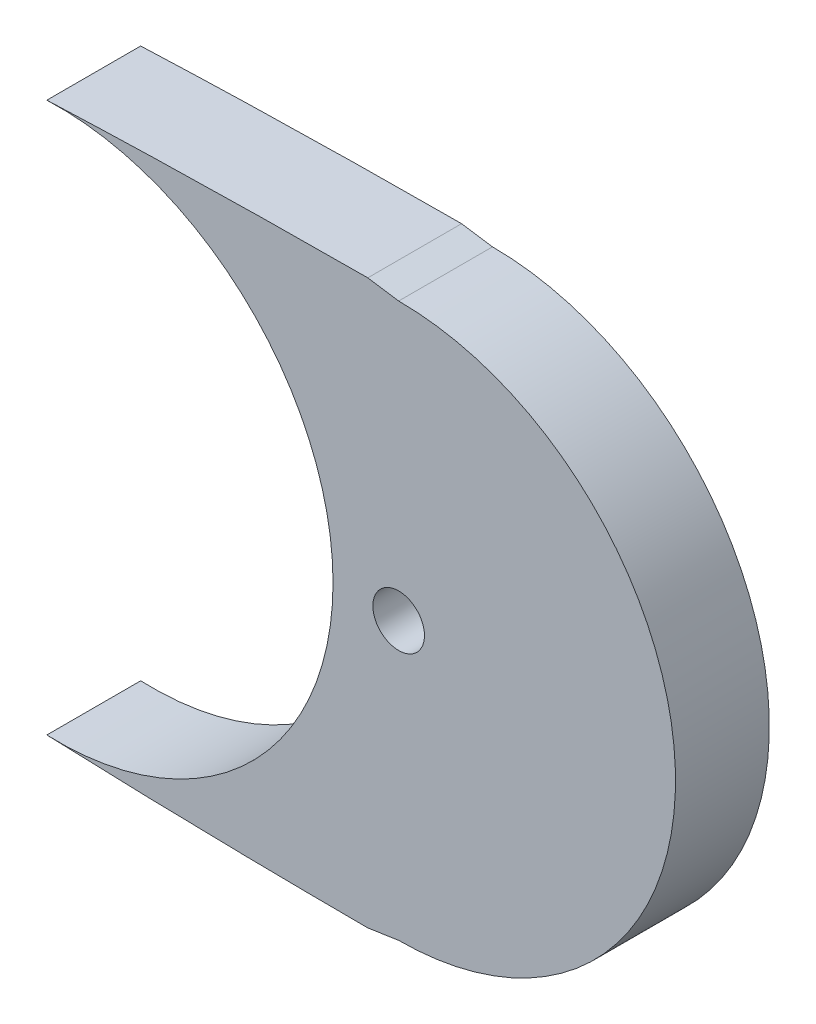
SolidWorks part; units mm, degrees
ref_plane "Front Plane" through (0, 0, 0) normal (0, 0, 1) x (1, 0, 0)
ref_plane "Top Plane" through (0, 0, 0) normal (0, 1, 0) x (1, 0, 0)
ref_plane "Right Plane" through (0, 0, 0) normal (1, 0, 0) x (0, 0, -1)
curve "Curve2"
  spline degree 3 poles (300, 0.378, 0) (299.8459, 0.3996, 0) (299.2303, 0.4859, 0) (297.8489, 0.6785, 0) (295.556, 0.9968, 0) (292.3657, 1.4334, 0) (288.2979, 1.9834, 0) (283.3772, 2.6357, 0) (277.6343, 3.3815, 0) (271.1045, 4.209, 0) (263.8281, 5.1072, 0) (255.8498, 6.0628, 0) (247.219, 7.0642, 0) (237.9888, 8.0979, 0) (228.216, 9.1511, 0) (217.9611, 10.2107, 0) (207.2872, 11.2632, 0) (196.2601, 12.2937, 0) (184.9478, 13.2887, 0) (173.4201, 14.2316, 0) (161.7479, 15.107, 0) (150.0032, 15.8986, 0) (138.2584, 16.5898, 0) (126.5858, 17.1634, 0) (115.0575, 17.6038, 0) (103.7442, 17.8968, 0) (92.7158, 18.028, 0) (82.0402, 17.9871, 0) (71.7831, 17.7661, 0) (62.0077, 17.3595, 0) (52.7741, 16.7661, 0) (44.1391, 15.9878, 0) (36.1555, 15.0306, 0) (28.872, 13.9026, 0) (22.3327, 12.6157, 0) (16.576, 11.1845, 0) (11.6345, 9.6228, 0) (7.5334, 7.9452, 0) (4.2857, 6.163, 0) (1.8965, 4.2728, 0) (0.3663, 2.2288, 0) (-0.1707, 0, 0) (0.3663, -2.2288, 0) (1.8965, -4.2728, 0) (4.2857, -6.163, 0) (7.5334, -7.9452, 0) (11.6345, -9.6228, 0) (16.576, -11.1845, 0) (22.3327, -12.6157, 0) (28.872, -13.9026, 0) (36.1555, -15.0306, 0) (44.1391, -15.9878, 0) (52.7741, -16.7661, 0) (62.0077, -17.3595, 0) (71.7831, -17.7661, 0) (82.0402, -17.9871, 0) (92.7158, -18.028, 0) (103.7442, -17.8968, 0) (115.0575, -17.6038, 0) (126.5858, -17.1634, 0) (138.2584, -16.5898, 0) (150.0032, -15.8986, 0) (161.7479, -15.107, 0) (173.4201, -14.2316, 0) (184.9478, -13.2887, 0) (196.2601, -12.2937, 0) (207.2872, -11.2632, 0) (217.9611, -10.2107, 0) (228.216, -9.1511, 0) (237.9888, -8.0979, 0) (247.219, -7.0642, 0) (255.8498, -6.0628, 0) (263.8281, -5.1072, 0) (271.1045, -4.209, 0) (277.6343, -3.3815, 0) (283.3772, -2.6357, 0) (288.2979, -1.9834, 0) (292.3657, -1.4334, 0) (295.556, -0.9968, 0) (297.8489, -0.6785, 0) (299.2303, -0.4859, 0) (299.8459, -0.3996, 0) (300, -0.378, 0) knots 0 0 0 0 0.000763 0.003048 0.006841 0.012116 0.018841 0.026973 0.03646 0.047243 0.059254 0.072417 0.086651 0.101866 0.117969 0.134858 0.152428 0.170572 0.189175 0.208122 0.227297 0.24658 0.265853 0.284997 0.303895 0.322433 0.340499 0.357984 0.374788 0.390812 0.405965 0.420162 0.433328 0.445394 0.456301 0.466004 0.474472 0.481696 0.487704 0.492583 0.496544 0.5 0.503456 0.507417 0.512296 0.518304 0.525528 0.533996 0.543699 0.554606 0.566672 0.579838 0.594035 0.609188 0.625212 0.642016 0.659501 0.677567 0.696105 0.715003 0.734147 0.75342 0.772703 0.791878 0.810825 0.829428 0.847572 0.865142 0.882031 0.898134 0.913349 0.927583 0.940746 0.952757 0.96354 0.973027 0.981159 0.987884 0.993159 0.996952 0.999237 1 1 1 1
sketch "Sketch2" plane through (0, 0, 0) normal (0, 0, 1) x (1, 0, 0)
  line L0 (0, 0) -> (300.3287, 0) construction
  line L9 (300, 0.378) -> (300, -0.378)
  line L17 (90, 18.0052) -> (90, -18.0052)
  line L20 (25.2817, 12.903) -> (25.2817, -12.903)
  line L21 (46.6322, 16.1183) -> (46.6322, -16.1183)
  line L22 (68.2099, 17.5933) -> (68.2099, -17.5933)
  line L23 (131.5031, 16.8963) -> (131.5031, -16.8963)
  line L24 (173.2123, 14.1909) -> (173.2123, -14.1909)
  line L25 (215.2898, -10.4186) -> (215.2898, 10.4186)
  line L26 (257.3103, -5.8439) -> (257.3103, 5.8439)
  arc A0 (300, -0.378) -> (300, 0.378) centre (299.947, 0) ccw
  arc A3 (45, 16.0354) -> (45, -16.0354) centre (46.6322, 0) ccw
  arc A5 (67.5, -17.5789) -> (67.5, 17.5789) centre (68.2099, 0) cw
  arc A6 (22.5, 12.5996) -> (22.5, -12.5996) centre (25.2817, 0) ccw
  arc A7 (258, -5.8031) -> (258, 5.8031) centre (257.3103, 0) cw
  arc A8 (216.3287, -10.3667) -> (216.3287, 10.3667) centre (215.2898, 0) cw
  arc A9 (174.3287, -14.147) -> (174.3287, 14.147) centre (173.2123, 0) cw
  arc A11 (132.3287, -16.8761) -> (132.3287, 16.8761) centre (131.5031, 0) cw
  arc A12 (90, -18.0052) -> (90, 18.0052) centre (89.9987, 0) cw
  arc A13 (22.5, 12.5996) -> (22.5, -12.5996) centre (25.2817, 0) cw
  arc A14 (45, 16.0354) -> (45, -16.0354) centre (46.6322, 0) cw
  arc A15 (67.5, 17.5789) -> (67.5, -17.5789) centre (68.2099, 0) cw
  arc A16 (90, -18.0052) -> (90, 18.0052) centre (90, 0) ccw
  arc A17 (132.3287, 16.8761) -> (132.3287, -16.8761) centre (131.5031, 0) cw
  arc A18 (174.3287, 14.147) -> (174.3287, -14.147) centre (173.2123, 0) cw
  arc A19 (216.3287, 10.3667) -> (216.3287, -10.3667) centre (215.2898, 0) cw
  arc A20 (257.9987, 5.8032) -> (257.9987, -5.8032) centre (257.309, 0) cw
  circle A21 centre (25.2817, 0) radius 12.903
  circle A22 centre (257.3103, 0) radius 5.8439
  circle A23 centre (68.2099, 0) radius 2.65
  circle A24 centre (90, 0) radius 1.65
  spline S0 degree 3 poles (925.2225, 2929.7557) (439.7439, -25.8231) (369.6404, -9.3304) (297.8489, 0.6785) (295.556, 0.9968) (292.3657, 1.4334) (288.2979, 1.9834) (283.3772, 2.6357) (277.6343, 3.3815) (271.1045, 4.209) (263.8281, 5.1072) (255.8498, 6.0628) (247.219, 7.0642) (237.9888, 8.0979) (228.216, 9.1511) (217.9611, 10.2107) (207.2872, 11.2632) (196.2601, 12.2937) (184.9478, 13.2887) (173.4201, 14.2316) (161.7479, 15.107) (150.0032, 15.8986) (138.2584, 16.5898) (126.5858, 17.1634) (115.0575, 17.6038) (103.7442, 17.8968) (92.7158, 18.028) (82.0402, 17.9871) (71.7831, 17.7661) (62.0077, 17.3595) (52.7741, 16.7661) (44.1391, 15.9878) (36.1555, 15.0306) (28.872, 13.9026) (22.3327, 12.6157) (16.576, 11.1845) (11.6345, 9.6228) (7.5334, 7.9452) (4.2857, 6.163) (1.8965, 4.2728) (0.3663, 2.2288) (-0.1707, 0) (0.3663, -2.2288) (1.8965, -4.2728) (4.2857, -6.163) (7.5334, -7.9452) (11.6345, -9.6228) (16.576, -11.1845) (22.3327, -12.6157) (28.872, -13.9026) (36.1555, -15.0306) (44.1391, -15.9878) (52.7741, -16.7661) (62.0077, -17.3595) (71.7831, -17.7661) (82.0402, -17.9871) (92.7158, -18.028) (103.7442, -17.8968) (115.0575, -17.6038) (126.5858, -17.1634) (138.2584, -16.5898) (150.0032, -15.8986) (161.7479, -15.107) (173.4201, -14.2316) (184.9478, -13.2887) (196.2601, -12.2937) (207.2872, -11.2632) (217.9611, -10.2107) (228.216, -9.1511) (237.9888, -8.0979) (247.219, -7.0642) (255.8498, -6.0628) (263.8281, -5.1072) (271.1045, -4.209) (277.6343, -3.3815) (283.3772, -2.6357) (288.2979, -1.9834) (292.3657, -1.4334) (295.556, -0.9968) (297.8489, -0.6785) (369.6396, 9.3303) (439.7423, 25.8227) (925.2055, -2929.6525) knots -0.348659 -0.348659 -0.348659 -0.348659 0.000763 0.003048 0.006841 0.012116 0.018841 0.026973 0.03646 0.047243 0.059254 0.072417 0.086651 0.101866 0.117969 0.134858 0.152428 0.170572 0.189175 0.208122 0.227297 0.24658 0.265853 0.284997 0.303895 0.322433 0.340499 0.357984 0.374788 0.390812 0.405965 0.420162 0.433328 0.445394 0.456301 0.466004 0.474472 0.481696 0.487704 0.492583 0.496544 0.5 0.503456 0.507417 0.512296 0.518304 0.525528 0.533996 0.543699 0.554606 0.566672 0.579838 0.594035 0.609188 0.625212 0.642016 0.659501 0.677567 0.696105 0.715003 0.734147 0.75342 0.772703 0.791878 0.810825 0.829428 0.847572 0.865142 0.882031 0.898134 0.913349 0.927583 0.940746 0.952757 0.96354 0.973027 0.981159 0.987884 0.993159 0.996952 0.999237 1.348655 1.348655 1.348655 1.348655 only from (300, 0.378) to (300, -0.378) construction
  spline S1 degree 3 poles (300, 0.378) (299.8459, 0.3996) (299.2303, 0.4859) (297.8489, 0.6785) (295.556, 0.9968) (292.3657, 1.4334) (288.2979, 1.9834) (283.3772, 2.6357) (277.6343, 3.3815) (271.1045, 4.209) (263.8281, 5.1072) (255.8498, 6.0628) (247.219, 7.0642) (237.9888, 8.0979) (228.216, 9.1511) (217.9611, 10.2107) (207.2872, 11.2632) (196.2601, 12.2937) (184.9478, 13.2887) (173.4201, 14.2316) (161.7479, 15.107) (150.0032, 15.8986) (138.2584, 16.5898) (126.5858, 17.1634) (115.0575, 17.6038) (103.7442, 17.8968) (92.7158, 18.028) (82.0402, 17.9871) (71.7831, 17.7661) (62.0077, 17.3595) (52.7741, 16.7661) (44.1391, 15.9878) (36.1555, 15.0306) (28.872, 13.9026) (22.3327, 12.6157) (16.576, 11.1845) (11.6345, 9.6228) (7.5334, 7.9452) (4.2857, 6.163) (1.8965, 4.2728) (0.3663, 2.2288) (-0.1707, 0) (0.3663, -2.2288) (1.8965, -4.2728) (4.2857, -6.163) (7.5334, -7.9452) (11.6345, -9.6228) (16.576, -11.1845) (22.3327, -12.6157) (28.872, -13.9026) (36.1555, -15.0306) (44.1391, -15.9878) (52.7741, -16.7661) (62.0077, -17.3595) (71.7831, -17.7661) (82.0402, -17.9871) (92.7158, -18.028) (103.7442, -17.8968) (115.0575, -17.6038) (126.5858, -17.1634) (138.2584, -16.5898) (150.0032, -15.8986) (161.7479, -15.107) (173.4201, -14.2316) (184.9478, -13.2887) (196.2601, -12.2937) (207.2872, -11.2632) (217.9611, -10.2107) (228.216, -9.1511) (237.9888, -8.0979) (247.219, -7.0642) (255.8498, -6.0628) (263.8281, -5.1072) (271.1045, -4.209) (277.6343, -3.3815) (283.3772, -2.6357) (288.2979, -1.9834) (292.3657, -1.4334) (295.556, -0.9968) (297.8489, -0.6785) (299.2303, -0.4859) (299.8459, -0.3996) (300, -0.378) knots 0 0 0 0 0.000763 0.003048 0.006841 0.012116 0.018841 0.026973 0.03646 0.047243 0.059254 0.072417 0.086651 0.101866 0.117969 0.134858 0.152428 0.170572 0.189175 0.208122 0.227297 0.24658 0.265853 0.284997 0.303895 0.322433 0.340499 0.357984 0.374788 0.390812 0.405965 0.420162 0.433328 0.445394 0.456301 0.466004 0.474472 0.481696 0.487704 0.492583 0.496544 0.5 0.503456 0.507417 0.512296 0.518304 0.525528 0.533996 0.543699 0.554606 0.566672 0.579838 0.594035 0.609188 0.625212 0.642016 0.659501 0.677567 0.696105 0.715003 0.734147 0.75342 0.772703 0.791878 0.810825 0.829428 0.847572 0.865142 0.882031 0.898134 0.913349 0.927583 0.940746 0.952757 0.96354 0.973027 0.981159 0.987884 0.993159 0.996952 0.999237 1 1 1 1
  point P47 (215.2898, 0)
  point P58 (257.3103, 0)
  point P61 (12.3787, 0)
  point P62 (62.7505, 0)
  dimension "D11" = 5.3
  dimension "D12" = 3.3
  dimension "D1" = 300.3287
  dimension "D2" = 89.9987
  dimension "D3" = 68.2099
  dimension "D4" = 46.6322
  dimension "D5" = 25.2817
  dimension "D6" = 168.8256
  dimension "D7" = 127.1164
  dimension "D8" = 85.0389
  dimension "D9" = 43.0184
  dimension "D10" = 50.3718
extrude "Boss-Extrude1" add sketch "Sketch2" along normal blind 6 contours A12 S1 A15 | A15 L0 L17 A12 | L0 A15 A12 L17 | A15 S1 A12 | L17 L0 A16 | L0 L17 A16
sketch "Sketch3" plane through (0, 0, 6) normal (0, 0, 1) x (1, 0, 0)
  line L0 (90, 17.7052) -> (88.0259, 18.0024)
  line L1 (90, -17.7052) -> (88.0259, -18.0024)
  arc A0 (90, -18.0052) -> (90, 18.0052) centre (90, 0) ccw construction
  arc A1 (90, -18.0052) -> (90, 18.0052) centre (90, 0) ccw
  arc A2 (90, -17.7052) -> (90, 17.7052) centre (90, 0) ccw
  arc A4 (67.5, -17.5789) -> (67.5, 17.5789) centre (68.2099, 0) ccw
  arc A5 (90, -18.0052) -> (90, 18.0052) centre (90, 0) ccw
  arc A6 (67.5, -17.5789) -> (67.5, 17.5789) centre (68.2099, 0) ccw
  arc A7 (90, -18.0052) -> (90, 18.0052) centre (90, 0) ccw
  spline S2 degree 3 poles (-238.8002, 2917.1978) (-404.6037, 171.2192) (-165.8113, -12.6473) (408.3425, -25.0171) (745.002, 249.2503) (674.9084, -2853.1343) knots -0.556272 -0.556272 -0.556272 -0.556272 0.625212 0.642016 2.260096 2.260096 2.260096 2.260096 only from (67.5, -17.5789) to (90, -18.0052)
  spline S3 degree 3 poles (674.9068, 2853.2067) (745.0072, -249.2545) (408.345, 25.0172) (-165.809, 12.6474) (-404.5992, -171.2158) (-238.805, -2917.119) knots -1.260108 -1.260108 -1.260108 -1.260108 0.357984 0.374788 1.556261 1.556261 1.556261 1.556261 only from (90, 18.0052) to (67.5, 17.5789)
  spline S4 degree 3 poles (67.5, -17.5789) (68.8749, -17.6344) (73.6741, -17.8069) (81.1746, -17.9685) (87.3004, -18.0054) (90, -18.0052) knots 0.618464 0.618464 0.618464 0.618464 0.625212 0.642016 0.655255 0.655255 0.655255 0.655255
  spline S5 degree 3 poles (90, 18.0052) (87.3004, 18.0054) (81.1746, 17.9685) (73.6741, 17.8069) (68.8749, 17.6344) (67.5, 17.5789) knots 0.344745 0.344745 0.344745 0.344745 0.357984 0.374788 0.381536 0.381536 0.381536 0.381536
  spline M6 degree 3 poles (300, 0.378) (299.8459, 0.3996) (299.2303, 0.4859) (297.8489, 0.6785) (295.556, 0.9968) (292.3657, 1.4334) (288.2979, 1.9834) (283.3772, 2.6357) (277.6343, 3.3815) (271.1045, 4.209) (263.8281, 5.1072) (255.8498, 6.0628) (247.219, 7.0642) (237.9888, 8.0979) (228.216, 9.1511) (217.9611, 10.2107) (207.2872, 11.2632) (196.2601, 12.2937) (184.9478, 13.2887) (173.4201, 14.2316) (161.7479, 15.107) (150.0032, 15.8986) (138.2584, 16.5898) (126.5858, 17.1634) (115.0575, 17.6038) (103.7442, 17.8968) (92.7158, 18.028) (82.0402, 17.9871) (71.7831, 17.7661) (62.0077, 17.3595) (52.7741, 16.7661) (44.1391, 15.9878) (36.1555, 15.0306) (28.872, 13.9026) (22.3327, 12.6157) (16.576, 11.1845) (11.6345, 9.6228) (7.5334, 7.9452) (4.2857, 6.163) (1.8965, 4.2728) (0.3663, 2.2288) (-0.1707, 0) (0.3663, -2.2288) (1.8965, -4.2728) (4.2857, -6.163) (7.5334, -7.9452) (11.6345, -9.6228) (16.576, -11.1845) (22.3327, -12.6157) (28.872, -13.9026) (36.1555, -15.0306) (44.1391, -15.9878) (52.7741, -16.7661) (62.0077, -17.3595) (71.7831, -17.7661) (82.0402, -17.9871) (92.7158, -18.028) (103.7442, -17.8968) (115.0575, -17.6038) (126.5858, -17.1634) (138.2584, -16.5898) (150.0032, -15.8986) (161.7479, -15.107) (173.4201, -14.2316) (184.9478, -13.2887) (196.2601, -12.2937) (207.2872, -11.2632) (217.9611, -10.2107) (228.216, -9.1511) (237.9888, -8.0979) (247.219, -7.0642) (255.8498, -6.0628) (263.8281, -5.1072) (271.1045, -4.209) (277.6343, -3.3815) (283.3772, -2.6357) (288.2979, -1.9834) (292.3657, -1.4334) (295.556, -0.9968) (297.8489, -0.6785) (299.2303, -0.4859) (299.8459, -0.3996) (300, -0.378) knots 0 0 0 0 0.000763 0.003048 0.006841 0.012116 0.018841 0.026973 0.03646 0.047243 0.059254 0.072417 0.086651 0.101866 0.117969 0.134858 0.152428 0.170572 0.189175 0.208122 0.227297 0.24658 0.265853 0.284997 0.303895 0.322433 0.340499 0.357984 0.374788 0.390812 0.405965 0.420162 0.433328 0.445394 0.456301 0.466004 0.474472 0.481696 0.487704 0.492583 0.496544 0.5 0.503456 0.507417 0.512296 0.518304 0.525528 0.533996 0.543699 0.554606 0.566672 0.579838 0.594035 0.609188 0.625212 0.642016 0.659501 0.677567 0.696105 0.715003 0.734147 0.75342 0.772703 0.791878 0.810825 0.829428 0.847572 0.865142 0.882031 0.898134 0.913349 0.927583 0.940746 0.952757 0.96354 0.973027 0.981159 0.987884 0.993159 0.996952 0.999237 1 1 1 1 only from (67.5, -17.5789) to (90, -18.0052)
  arc M7 (90, -18.0052) -> (90, 18.0052) centre (90, 0) ccw
  spline M8 degree 3 poles (300, 0.378) (299.8459, 0.3996) (299.2303, 0.4859) (297.8489, 0.6785) (295.556, 0.9968) (292.3657, 1.4334) (288.2979, 1.9834) (283.3772, 2.6357) (277.6343, 3.3815) (271.1045, 4.209) (263.8281, 5.1072) (255.8498, 6.0628) (247.219, 7.0642) (237.9888, 8.0979) (228.216, 9.1511) (217.9611, 10.2107) (207.2872, 11.2632) (196.2601, 12.2937) (184.9478, 13.2887) (173.4201, 14.2316) (161.7479, 15.107) (150.0032, 15.8986) (138.2584, 16.5898) (126.5858, 17.1634) (115.0575, 17.6038) (103.7442, 17.8968) (92.7158, 18.028) (82.0402, 17.9871) (71.7831, 17.7661) (62.0077, 17.3595) (52.7741, 16.7661) (44.1391, 15.9878) (36.1555, 15.0306) (28.872, 13.9026) (22.3327, 12.6157) (16.576, 11.1845) (11.6345, 9.6228) (7.5334, 7.9452) (4.2857, 6.163) (1.8965, 4.2728) (0.3663, 2.2288) (-0.1707, 0) (0.3663, -2.2288) (1.8965, -4.2728) (4.2857, -6.163) (7.5334, -7.9452) (11.6345, -9.6228) (16.576, -11.1845) (22.3327, -12.6157) (28.872, -13.9026) (36.1555, -15.0306) (44.1391, -15.9878) (52.7741, -16.7661) (62.0077, -17.3595) (71.7831, -17.7661) (82.0402, -17.9871) (92.7158, -18.028) (103.7442, -17.8968) (115.0575, -17.6038) (126.5858, -17.1634) (138.2584, -16.5898) (150.0032, -15.8986) (161.7479, -15.107) (173.4201, -14.2316) (184.9478, -13.2887) (196.2601, -12.2937) (207.2872, -11.2632) (217.9611, -10.2107) (228.216, -9.1511) (237.9888, -8.0979) (247.219, -7.0642) (255.8498, -6.0628) (263.8281, -5.1072) (271.1045, -4.209) (277.6343, -3.3815) (283.3772, -2.6357) (288.2979, -1.9834) (292.3657, -1.4334) (295.556, -0.9968) (297.8489, -0.6785) (299.2303, -0.4859) (299.8459, -0.3996) (300, -0.378) knots 0 0 0 0 0.000763 0.003048 0.006841 0.012116 0.018841 0.026973 0.03646 0.047243 0.059254 0.072417 0.086651 0.101866 0.117969 0.134858 0.152428 0.170572 0.189175 0.208122 0.227297 0.24658 0.265853 0.284997 0.303895 0.322433 0.340499 0.357984 0.374788 0.390812 0.405965 0.420162 0.433328 0.445394 0.456301 0.466004 0.474472 0.481696 0.487704 0.492583 0.496544 0.5 0.503456 0.507417 0.512296 0.518304 0.525528 0.533996 0.543699 0.554606 0.566672 0.579838 0.594035 0.609188 0.625212 0.642016 0.659501 0.677567 0.696105 0.715003 0.734147 0.75342 0.772703 0.791878 0.810825 0.829428 0.847572 0.865142 0.882031 0.898134 0.913349 0.927583 0.940746 0.952757 0.96354 0.973027 0.981159 0.987884 0.993159 0.996952 0.999237 1 1 1 1 only from (90, 18.0052) to (67.5, 17.5789)
  dimension "D1" = 0
  dimension "D2" = 0.3
extrude "Cut-Extrude1" cut sketch "Sketch3" against normal through all contours A2 L1 L0 M6 M7 M8
